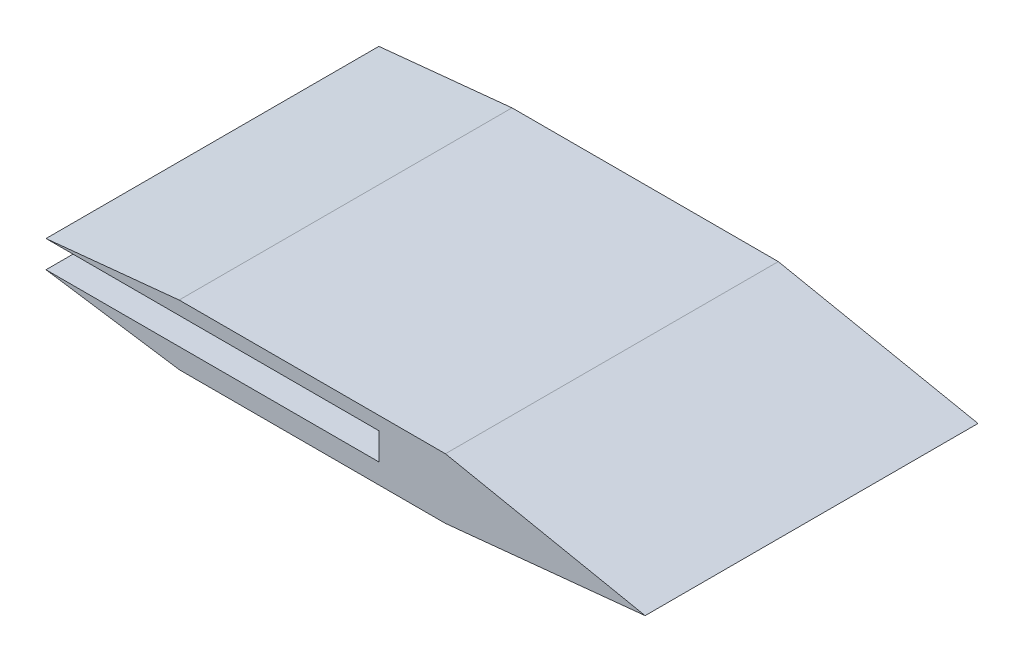
SolidWorks part; units mm, degrees
ref_plane "Přední rovina" through (0, 0, 0) normal (0, 0, 1) x (1, 0, 0)
ref_plane "Horní rovina" through (0, 0, 0) normal (0, 1, 0) x (1, 0, 0)
ref_plane "Pravá rovina" through (0, 0, 0) normal (1, 0, 0) x (0, 0, -1)
sketch "Skica1" plane through (0, 0, 0) normal (0, 0, 1) x (1, 0, 0)
  line L0 (0, 0) -> (20, 2)
  line L1 (20, 2) -> (60, 2)
  line L2 (60, 2) -> (90, -4.06)
  line L3 (90, -4.06) -> (60, -7.06)
  line L6 (0, -4.06) -> (50, -4.06)
  line L7 (50, -4.06) -> (50, 0)
  line L8 (50, 0) -> (0, 0)
  line L9 (50, -4.06) -> (113.4883, -4.06) construction
  line L10 (60, -7.06) -> (20, -7.06)
  line L11 (20, -7.06) -> (0, -4.06)
  dimension "D1" = 4.06
  dimension "D2" = 3
  dimension "D3" = 2
  dimension "D4" = 20
  dimension "D5" = 20
  dimension "D6" = 50
  dimension "D7" = 50
  dimension "D8" = 40
  dimension "D9" = 40
extrude "Přidat vysunutím1" add sketch "Skica1" along normal blind 50
